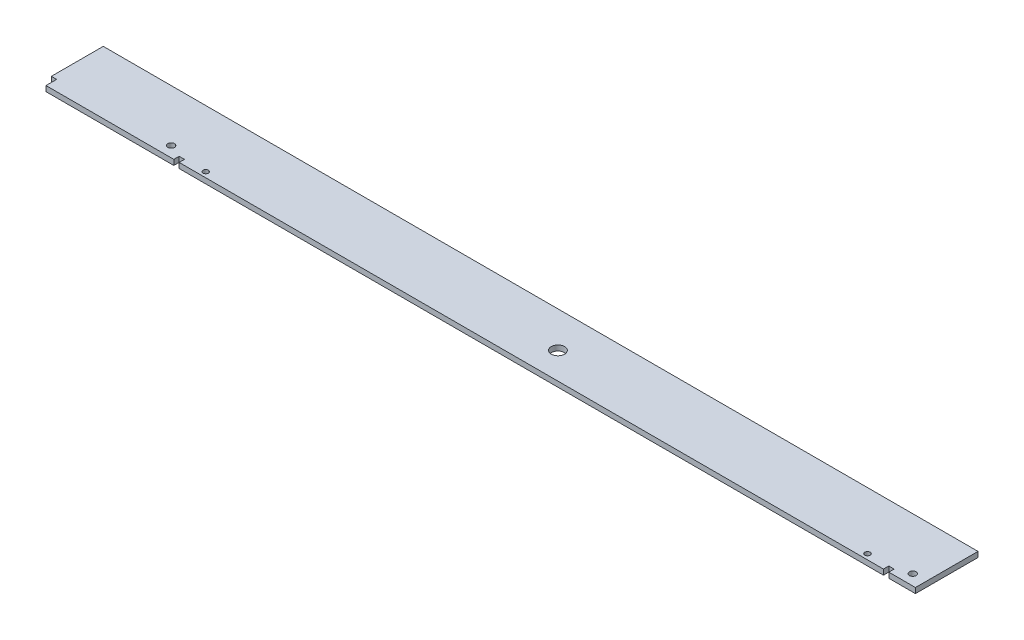
SolidWorks part; units mm, degrees
material "Pine"
ref_plane "Front Plane" through (0, 0, 0) normal (0, 0, 1) x (1, 0, 0)
ref_plane "Top Plane" through (0, 0, 0) normal (0, 1, 0) x (1, 0, 0)
ref_plane "Right Plane" through (0, 0, 0) normal (1, 0, 0) x (0, 0, -1)
sketch "Sketch1" plane through (-317.4166, 0, 154.9101) normal (0, 1, 0) x (-1, 0, 0)
  line L0 (-187.5362, 25.475) -> (-167.5362, 25.475)
  line L1 (-187.5362, 25.475) -> (-187.5362, -21.525)
  line L2 (-187.5362, -21.525) -> (469.4638, -21.525)
  line L3 (469.4638, 25.475) -> (469.4638, -21.525)
  line L4 (-167.5362, 25.475) -> (-167.5362, 21.475)
  line L5 (-167.5362, 21.475) -> (-163.5362, 21.475)
  line L6 (-163.5362, 21.475) -> (-163.5362, 25.475)
  line L7 (-163.5362, 25.475) -> (365.4638, 25.475)
  line L8 (365.4638, 25.475) -> (365.4638, 21.475)
  line L9 (365.4638, 21.475) -> (369.4638, 21.475)
  line L10 (369.4638, 21.475) -> (369.4638, 25.475)
  line L11 (369.4638, 25.475) -> (469.4638, 25.475)
  circle A0 centre (379.4638, 17.475) radius 2.5
  circle A1 centre (-177.5362, 17.475) radius 2.5
  circle A2 centre (349.4638, 21.475) radius 2
  circle A3 centre (-147.5362, 21.475) radius 2
  circle A4 centre (100.9638, 5.475) radius 5
  dimension "D4" = 5
  dimension "D6" = 5
  dimension "D8" = 4
  dimension "D17" = 4
  dimension "D23" = 10
  dimension "D1" = 657
  dimension "D2" = 47
  dimension "D3" = 90
  dimension "D5" = 8
  dimension "D7" = 10
  dimension "D9" = 120
  dimension "D10" = 4
  dimension "D11" = 100
  dimension "D12" = 4
  dimension "D13" = 4
  dimension "D14" = 20
  dimension "D15" = 4
  dimension "D16" = 4
  dimension "D18" = 40
  dimension "D19" = 4
  dimension "D20" = 16
  dimension "D21" = 8
  dimension "D22" = 557
  dimension "D24" = 288.5
  dimension "D25" = 27
extrude "Boss-Extrude1" add sketch "Sketch1" along normal blind 4
sketch "Sketch2" plane through (0, 0, 0) normal (0, -1, 0) x (1, 0, 0)
  line L1 (-786.8803, 180.3852) -> (-782.8803, 180.3852)
  line L2 (-786.8803, 180.3852) -> (-786.8803, 172.3852)
  line L3 (-786.8803, 172.3852) -> (-782.8803, 172.3852)
  line L4 (-782.8803, 180.3852) -> (-782.8803, 172.3852)
  dimension "D1" = 8
  dimension "D2" = 4
extrude "Cut-Extrude1" cut sketch "Sketch2" against normal blind 4
